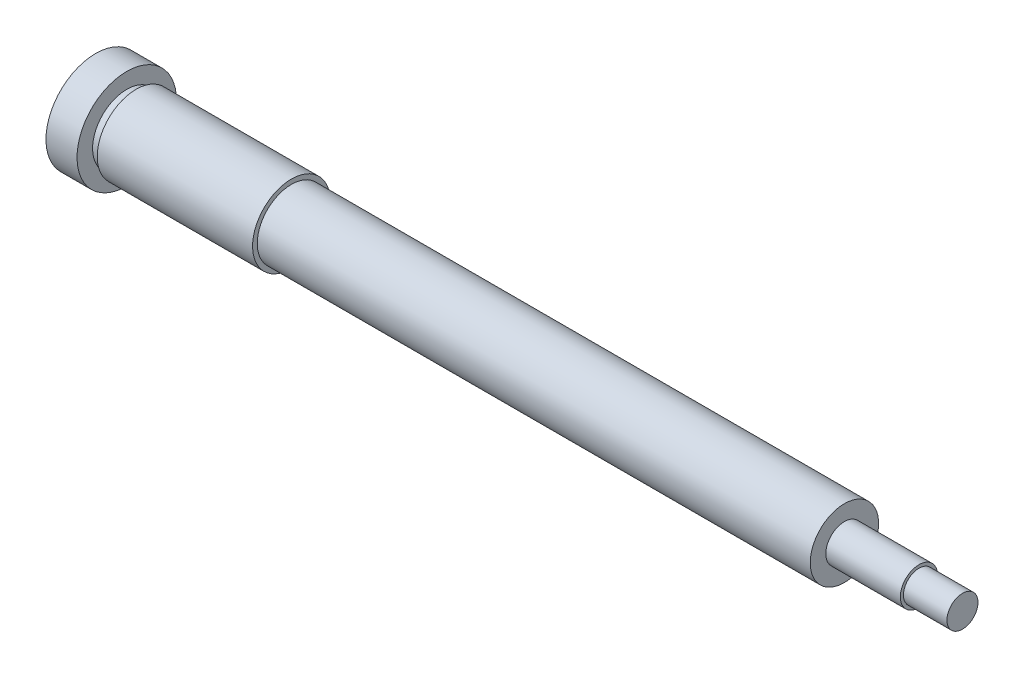
SolidWorks part; units mm, degrees
ref_plane "Front Plane" through (0, 0, 0) normal (0, 0, 1) x (1, 0, 0)
ref_plane "Top Plane" through (0, 0, 0) normal (0, 1, 0) x (1, 0, 0)
ref_plane "Right Plane" through (0, 0, 0) normal (1, 0, 0) x (0, 0, -1)
sketch "Sketch1" plane through (0, 0, 0) normal (0, 0, 1) x (1, 0, 0)
  line L0 (0, 0) -> (0, 16)
  line L1 (0, 16) -> (10, 16)
  line L2 (10, 16) -> (10, 11)
  line L3 (10, 11) -> (13, 11)
  line L4 (13, 11) -> (13, 12.5)
  line L5 (13, 12.5) -> (63, 12.5)
  line L6 (63, 12.5) -> (63, 11)
  line L7 (63, 11) -> (241, 11)
  line L8 (241, 11) -> (241, 6)
  line L9 (241, 6) -> (265, 6)
  line L10 (265, 6) -> (265, 5)
  line L11 (265, 5) -> (279, 5)
  line L12 (279, 5) -> (279, 0)
  line L13 (279, 0) -> (0, 0)
  dimension "D1" = 50
  dimension "D2" = 3
  dimension "D3" = 10
  dimension "D4" = 16
  dimension "D5" = 12.5
  dimension "D6" = 11
  dimension "D7" = 5
  dimension "D8" = 6
  dimension "D9" = 24
  dimension "D10" = 14
  dimension "D11" = 279
revolve "Revolve1" add sketch "Sketch1" angle 360 about L13
